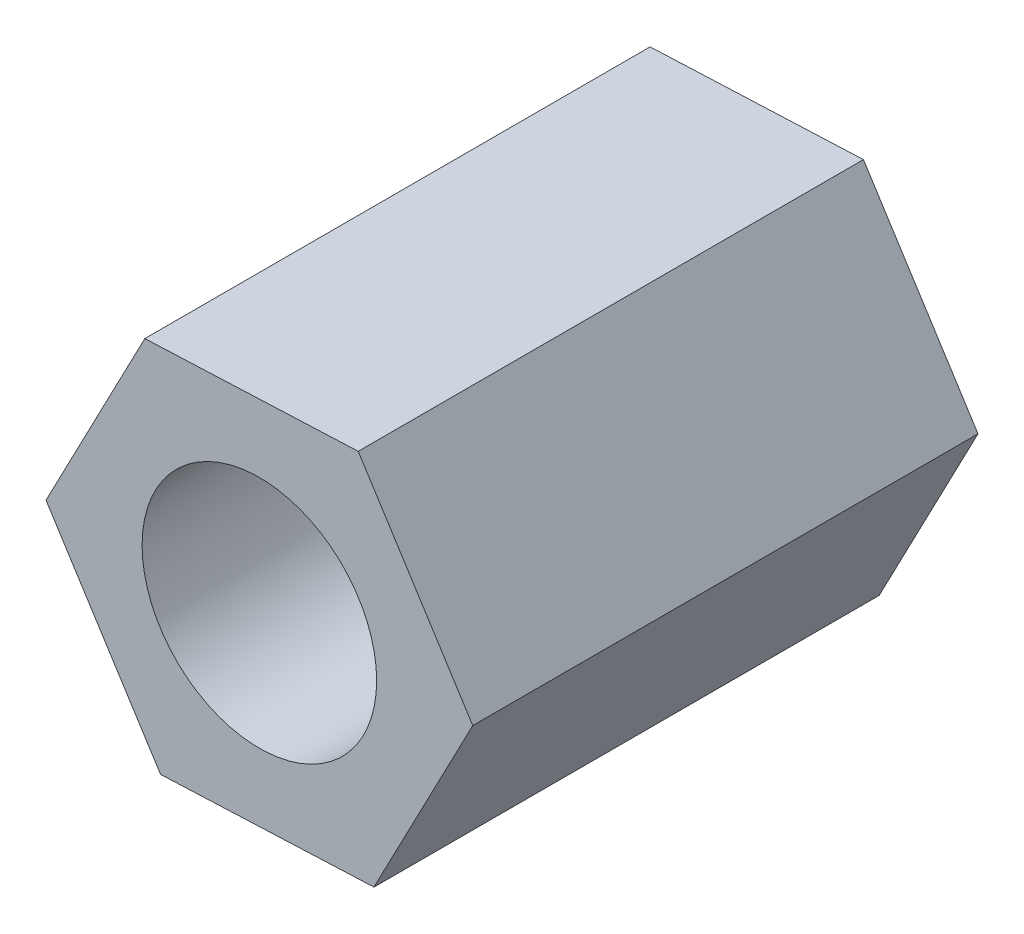
SolidWorks part; units mm, degrees
ref_plane "前视基准面" through (0, 0, 0) normal (0, 0, 1) x (1, 0, 0)
ref_plane "上视基准面" through (0, 0, 0) normal (0, 1, 0) x (1, 0, 0)
ref_plane "右视基准面" through (0, 0, 0) normal (1, 0, 0) x (0, 0, -1)
sketch "草图1" plane through (0, 0, 0) normal (0, 0, 1) x (1, 0, 0)
  line L1 (-12.6957, 19.9788) -> (-23.65, -1.0054)
  line L2 (-23.65, -1.0054) -> (-10.9543, -20.9842)
  line L3 (-10.9543, -20.9842) -> (12.6957, -19.9788)
  line L4 (12.6957, -19.9788) -> (23.65, 1.0054)
  line L5 (23.65, 1.0054) -> (10.9543, 20.9842)
  line L6 (10.9543, 20.9842) -> (-12.6957, 19.9788)
  circle A0 centre (0, 0) radius 20.5 construction
  dimension "D1" = 41
  dimension "D2" = 47.3
extrude "凸台-拉伸1" add sketch "草图1" along normal blind 56
sketch "草图2" plane through (0, 0, 56) normal (0, 0, 1) x (1, 0, 0)
  circle A0 centre (0, 0) radius 13
  dimension "D1" = 26
extrude "切除-拉伸1" cut sketch "草图2" against normal blind 27
sketch "草图3" plane through (0, 0, 29) normal (0, 0, 1) x (1, 0, 0)
  circle A0 centre (0, 0) radius 11.1
  dimension "D1" = 22.2
extrude "切除-拉伸2" cut sketch "草图3" against normal through all
